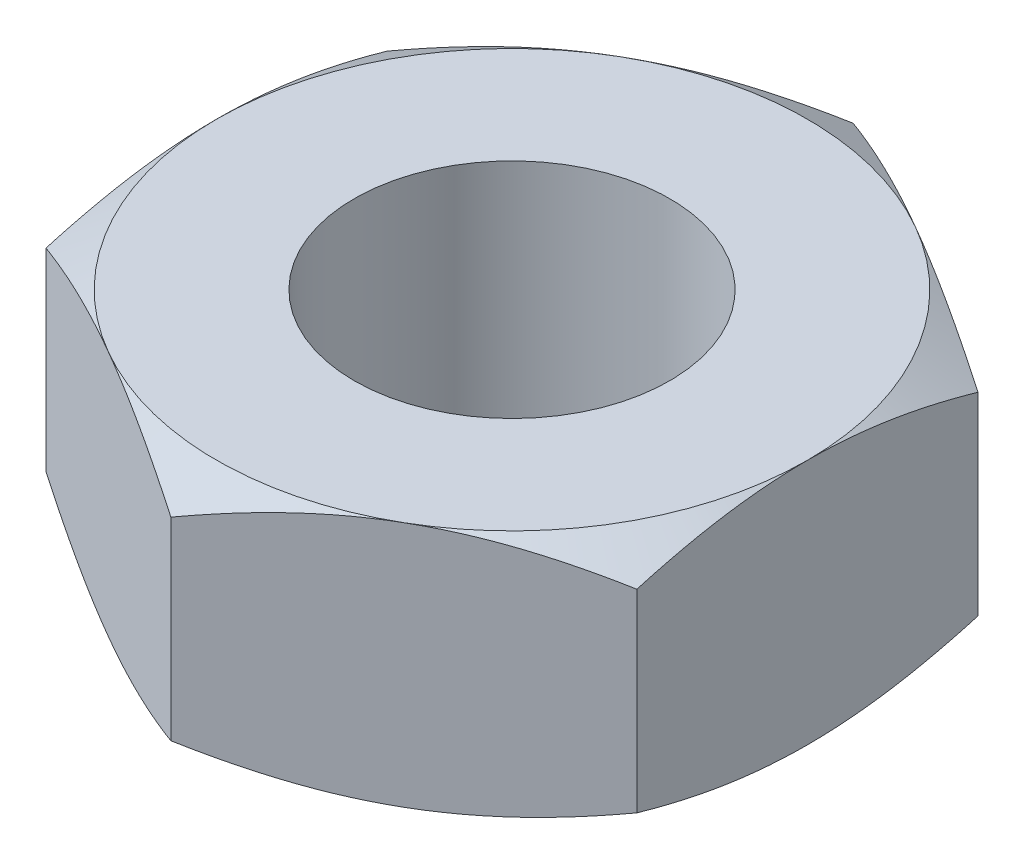
SolidWorks part; units mm, degrees
ref_plane "Front Plane" through (0, 0, 0) normal (0, 0, 1) x (1, 0, 0)
ref_plane "Top Plane" through (0, 0, 0) normal (0, 1, 0) x (1, 0, 0)
ref_plane "Right Plane" through (0, 0, 0) normal (1, 0, 0) x (0, 0, -1)
sketch "Sketch1" plane through (0, 0, 0) normal (0, 1, 0) x (1, 0, 0)
  line L1 (0, 40) -> (-34.641, 20)
  line L2 (-34.641, 20) -> (-34.641, -20)
  line L3 (-34.641, -20) -> (0, -40)
  line L4 (0, -40) -> (34.641, -20)
  line L5 (34.641, -20) -> (34.641, 20)
  line L6 (34.641, 20) -> (0, 40)
  circle A0 centre (0, 0) radius 34.641 construction
  circle A1 centre (0, 0) radius 18.5
  dimension "D2" = 37
  dimension "D1" = 80
extrude "Boss-Extrude1" add sketch "Sketch1" along normal mid plane 28.9
sketch "Sketch2" plane through (0, 14.45, 0) normal (0, 1, 0) x (1, 0, 0)
  line L0 (-34.641, 20) -> (-34.641, -20) construction
  circle A0 centre (0, 0) radius 34.641
extrude "Cut-Extrude1" cut sketch "Sketch2" against normal through all draft 60 flip side to cut
mirror "Mirror1" about plane through (0, 0, 0) normal (0, 1, 0) of "Cut-Extrude1"
